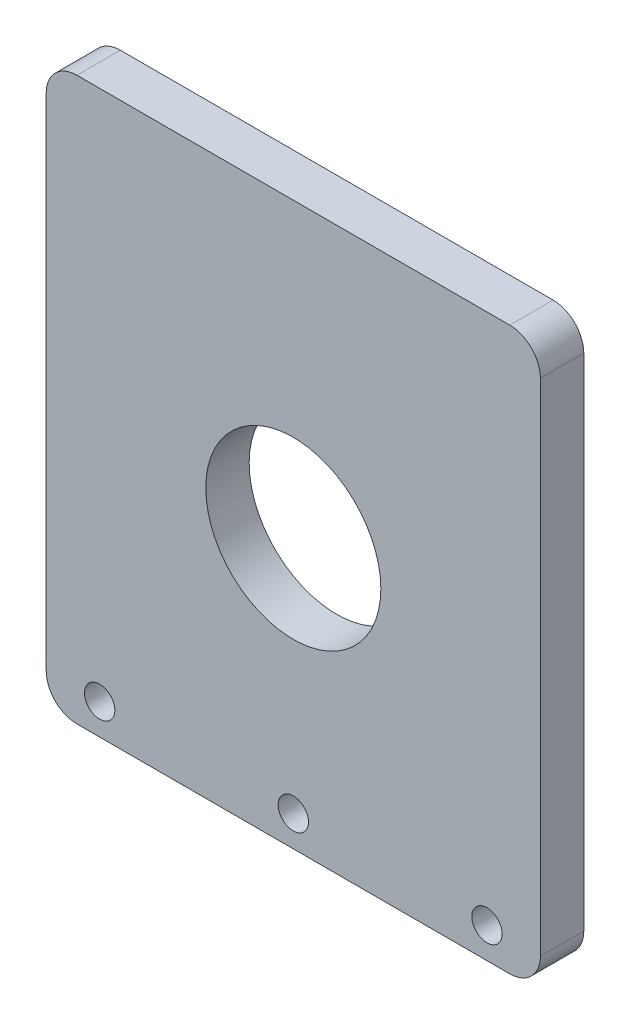
SolidWorks part; units mm, degrees
ref_plane "Front Plane" through (0, 0, 0) normal (0, 0, 1) x (1, 0, 0)
ref_plane "Top Plane" through (0, 0, 0) normal (0, 1, 0) x (1, 0, 0)
ref_plane "Right Plane" through (0, 0, 0) normal (1, 0, 0) x (0, 0, -1)
sketch "Sketch1" plane through (0, 0, 0) normal (0, 0, 1) x (1, 0, 0)
  line L4 (-4581.5973, 2459.2732) -> (-4581.5973, 2377.2204)
  line L5 (-4662.6233, 2459.2732) -> (-4662.6233, 2377.2204)
  line L6 (-4586.6265, 2372.1912) -> (-4657.5941, 2372.1912)
  line L7 (-4586.6265, 2464.3024) -> (-4657.5941, 2464.3024)
  circle A0 centre (-4590.3603, 2377.2204) radius 2.4892 construction
  circle A1 centre (-4590.3603, 2377.2204) radius 2.4892
  circle A8 centre (-4622.1103, 2416.2856) radius 14.351
  circle A9 centre (-4622.1103, 2377.2204) radius 2.4892
  arc A10 (-4662.6233, 2377.2204) -> (-4657.5941, 2372.1912) centre (-4657.5941, 2377.2204) ccw
  arc A11 (-4586.6265, 2372.1912) -> (-4581.5973, 2377.2204) centre (-4586.6265, 2377.2204) ccw
  arc A12 (-4657.5941, 2464.3024) -> (-4662.6233, 2459.2732) centre (-4657.5941, 2459.2732) ccw
  arc A13 (-4581.5973, 2459.2732) -> (-4586.6265, 2464.3024) centre (-4586.6265, 2459.2732) ccw
  circle A14 centre (-4590.3603, 2377.2204) radius 2.4892
  circle A15 centre (-4653.8603, 2377.2204) radius 2.4892
  point P23 (0, 0.001)
  point P24 (0.001, 0.001)
  point P25 (0.001, 0)
extrude "Boss-Extrude1" add sketch "Sketch1" along normal blind 7.112 contours L4 A13 L7 A12 L5 A10 L6 A11 A15 A1 A8 A9
